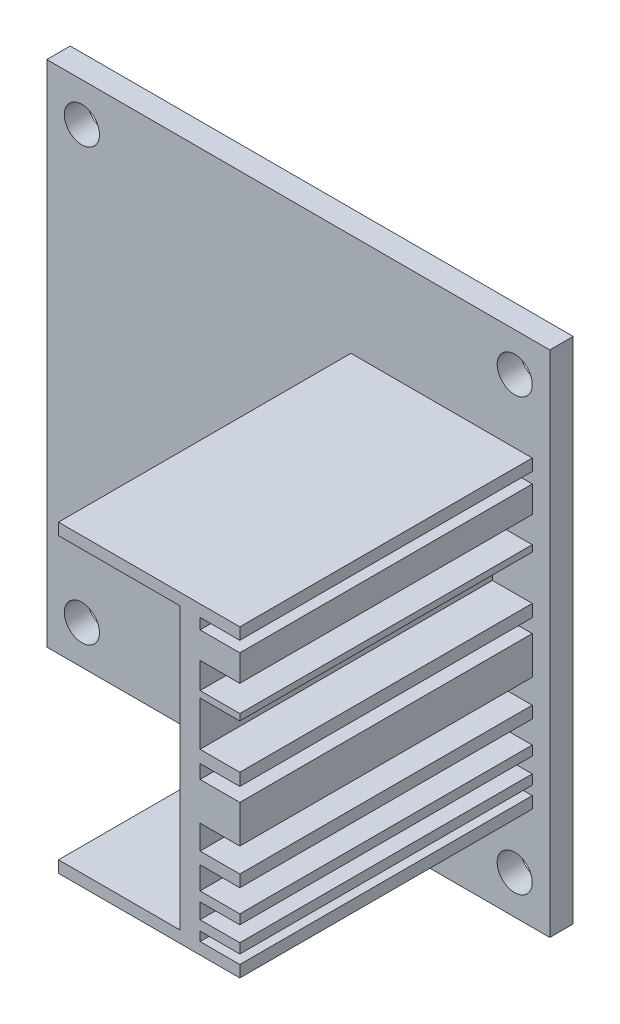
SolidWorks part; units mm, degrees
ref_plane "前视基准面" through (0, 0, 0) normal (0, 0, 1) x (1, 0, 0)
ref_plane "上视基准面" through (0, 0, 0) normal (0, 1, 0) x (1, 0, 0)
ref_plane "右视基准面" through (0, 0, 0) normal (1, 0, 0) x (0, 0, -1)
sketch "草图1" plane through (0, 0, 0) normal (0, 0, 1) x (1, 0, 0)
  line L1 (-21.5, -21.75) -> (21.5, -21.75)
  line L2 (-21.5, -21.75) -> (-21.5, 21.75)
  line L3 (-21.5, 21.75) -> (21.5, 21.75)
  line L4 (21.5, -21.75) -> (21.5, 21.75)
  line L5 (0, 21.75) -> (0, -21.75) construction
  line L6 (-21.5, 0) -> (21.5, 0) construction
  circle A0 centre (-18.5, 18.4317) radius 1.5
  circle A1 centre (18.5, -18.4317) radius 1.5
  circle A2 centre (-18.5, -18.4317) radius 1.5
  circle A3 centre (18.5, 18.4317) radius 1.5
  point P0 (0, 0)
  dimension "D1" = 43
  dimension "D6" = 3
  dimension "D7" = 3
  dimension "D2" = 43.5
  dimension "D3" = 37
  dimension "D10" = 3
extrude "凸台-拉伸1" add sketch "草图1" along normal blind 2
sketch "草图2" plane through (0, 0, 2) normal (0, 0, 1) x (1, 0, 0)
  line L0 (21.5, -21.75) -> (21.5, 21.75) construction
  line L1 (4.5, 13) -> (20, 13)
  line L2 (4.5, 13) -> (4.5, -13)
  line L3 (4.5, -13) -> (20, -13)
  line L4 (20, 13) -> (20, -13)
  line L5 (-21.5, -21.75) -> (21.5, -21.75) construction
  dimension "D1" = 15.5
  dimension "D2" = 1.5
  dimension "D3" = 8.75
  dimension "D4" = 26
extrude "凸台-拉伸2" add sketch "草图2" along normal blind 25
sketch "草图3" plane through (0, 0, 27) normal (0, 0, 1) x (1, 0, 0)
  line L0 (4.5, 13) -> (4.5, -13) construction
  line L1 (4.5, 12) -> (14.9, 12)
  line L2 (4.5, 12) -> (4.5, -12)
  line L3 (4.5, -12) -> (14.9, -12)
  line L4 (14.9, 12) -> (14.9, -12)
  line L5 (20, 13) -> (4.5, 13) construction
  line L6 (4.5, -13) -> (20, -13) construction
  line L7 (20, -13) -> (20, 13) construction
  line L8 (20, 12) -> (16.6, 12)
  line L9 (20, 12) -> (20, 11.0732)
  line L10 (20, -12) -> (16.6, -12)
  line L11 (16.6, 12) -> (16.6, 11.0732)
  line L12 (16.6, 11.0732) -> (20, 11.0732)
  line L13 (16.6, -11.2255) -> (20, -11.2255)
  line L14 (16.6, 8.8149) -> (20, 8.8149)
  line L15 (16.6, 8.8149) -> (16.6, 6.5788)
  line L16 (16.6, 6.5788) -> (20, 6.5788)
  line L17 (20, 8.8149) -> (20, 6.5788)
  line L18 (16.6, 6.0303) -> (20, 6.0303)
  line L19 (16.6, 6.0303) -> (16.6, 2.2332)
  line L20 (16.6, 2.2332) -> (20, 2.2332)
  line L21 (20, 6.0303) -> (20, 2.2332)
  line L22 (16.6, 1.1785) -> (20, 1.1785)
  line L23 (16.6, 1.1785) -> (16.6, 0)
  line L24 (16.6, 0) -> (20, 0)
  line L25 (20, 1.1785) -> (20, 0)
  line L27 (16.6, -10.3886) -> (20, -10.3886)
  line L28 (16.6, -10.3886) -> (16.6, -9.066)
  line L29 (16.6, -9.066) -> (20, -9.066)
  line L30 (20, -10.3886) -> (20, -9.066)
  line L31 (16.6, -8.2521) -> (20, -8.2521)
  line L32 (16.6, -8.2521) -> (16.6, -6.3191)
  line L33 (16.6, -6.3191) -> (20, -6.3191)
  line L34 (20, -8.2521) -> (20, -6.3191)
  line L35 (16.6, -5.3017) -> (20, -5.3017)
  line L36 (16.6, -5.3017) -> (16.6, -3.233)
  line L37 (16.6, -3.233) -> (20, -3.233)
  line L38 (20, -5.3017) -> (20, -3.233)
  line L44 (20, -11.2255) -> (20, -12)
  line L49 (16.6, -11.2255) -> (16.6, -12)
  dimension "D1" = 1
  dimension "D2" = 1
  dimension "D3" = 10.4
  dimension "D4" = 3.4
extrude "切除-拉伸1" cut sketch "草图3" against normal blind 25
